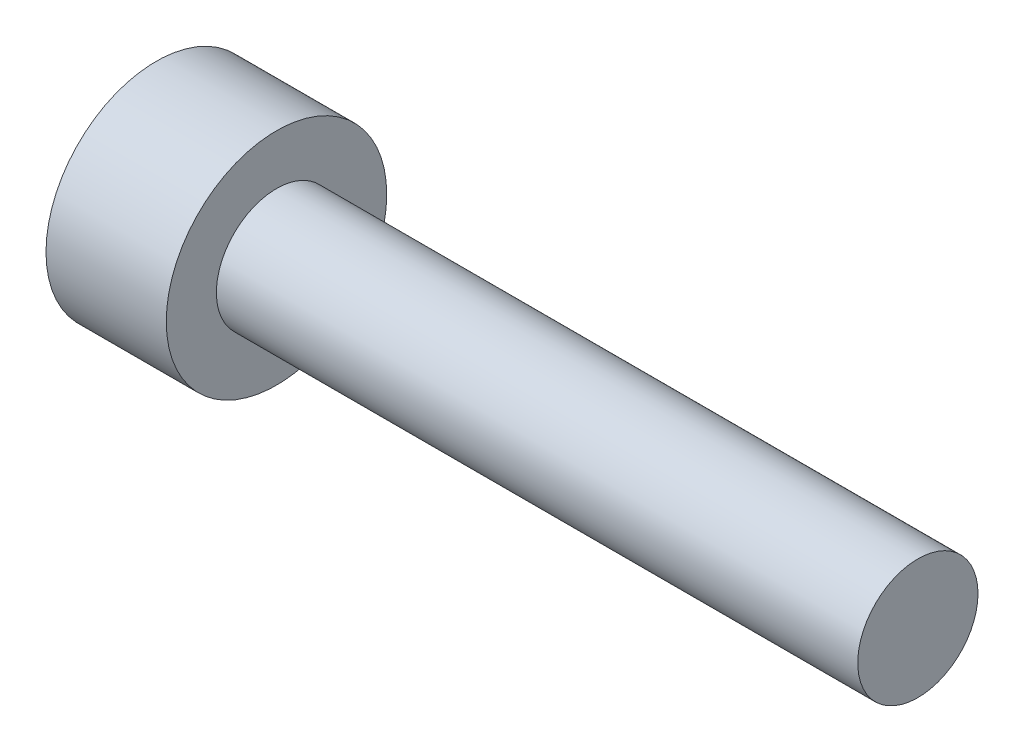
SolidWorks part; units mm, degrees
material "1.4000 (X6Cr13)"
ref_plane "Ebene vorne" through (0, 0, 0) normal (1, 0, 0) x (0, 1, 0)
ref_plane "Ebene oben" through (0, 0, 0) normal (0, 0, 1) x (0, 1, 0)
ref_plane "Ebene rechts" through (0, 0, 0) normal (0, 1, 0) x (-1, 0, 0)
sketch "Skizze1" plane through (0, 0, 0) normal (1, 0, 0) x (0, 1, 0)
  circle A0 centre (0, 0) radius 2.75
extrude "Aufsatz-Linear austragen1" add sketch "Skizze1" along normal blind 3 contours A0
sketch "Skizze2" plane through (0, 0, 0) normal (1, 0, 0) x (0, 1, 0)
  circle A0 centre (0, 0) radius 1.5
extrude "Aufsatz-Linear austragen2" add sketch "Skizze2" along normal blind 16 from offset 3
